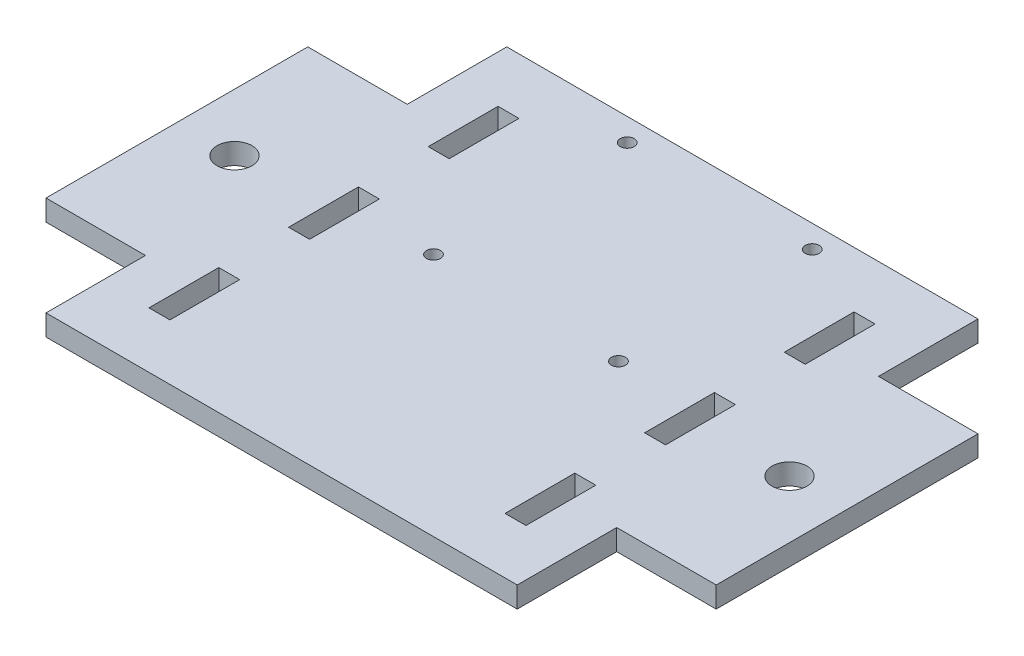
SolidWorks part; units mm, degrees
ref_plane "Front Plane" through (0, 0, 0) normal (0, 0, 1) x (1, 0, 0)
ref_plane "Top Plane" through (0, 0, 0) normal (0, 1, 0) x (1, 0, 0)
ref_plane "Right Plane" through (0, 0, 0) normal (1, 0, 0) x (0, 0, -1)
sketch "Sketch1" plane through (0, 0, 0) normal (0, 1, 0) x (1, 0, 0)
  line L0 (-48, 0) -> (48, 0) construction
  line L1 (-48, 33) -> (48, 33)
  line L2 (-48, 33) -> (-48, -33)
  line L3 (-48, -33) -> (48, -33)
  line L4 (48, 33) -> (48, -33)
  line L5 (-48, 33) -> (48, -33) construction
  line L6 (-48, -33) -> (48, 33) construction
  line L7 (0, 33) -> (0, -33) construction
  line L9 (17, 0) -> (-9.5, 0) construction
  line L13 (-13.25, 29.75) -> (13.25, 29.75) construction
  line L14 (-13.25, 29.75) -> (-13.25, 2) construction
  line L15 (-13.25, 2) -> (13.25, 2) construction
  line L16 (13.25, 29.75) -> (13.25, 2) construction
  circle A4 centre (-39.75, 0) radius 2.5
  circle A5 centre (39.75, 0) radius 2.5
  circle A6 centre (-13.25, 29.75) radius 1
  circle A7 centre (-13.25, 2) radius 1
  circle A8 centre (13.25, 2) radius 1
  circle A9 centre (13.25, 29.75) radius 1
  circle A10 centre (0, 0) radius 6 construction
  point P0 (0, 0)
  dimension "D6" = 27.75
  dimension "D7" = 26.5
  dimension "D8" = 2
  dimension "D9" = 2
  dimension "D10" = 5
  dimension "D11" = 8.25
  dimension "D12" = 12
  dimension "D4" = 2
  dimension "D5" = 2
  dimension "D13" = 34.75
  dimension "D1" = 96
  dimension "D2" = 66
  dimension "D3" = 2
extrude "Boss-Extrude1" add sketch "Sketch1" along normal blind 3
sketch "Sketch2" plane through (0, 3, 0) normal (0, 1, 0) x (1, 0, 0)
  line L0 (-48, 0) -> (48, 0) construction
  line L1 (-48, 33) -> (-48, -33) construction
  line L2 (48, -33) -> (48, 33) construction
  line L3 (0, 33) -> (0, -33) construction
  line L4 (48, 33) -> (-48, 33) construction
  line L5 (-48, -33) -> (48, -33) construction
  line L6 (33.75, 33) -> (33.75, 18.75)
  line L7 (-48, 33) -> (-33.75, 33)
  line L8 (-48, 33) -> (-48, 18.75)
  line L9 (-48, 18.75) -> (-33.75, 18.75)
  line L10 (-33.75, 33) -> (-33.75, 18.75)
  line L11 (48, 18.75) -> (33.75, 18.75)
  line L12 (48, 33) -> (48, 18.75)
  line L13 (48, 33) -> (33.75, 33)
  line L14 (48, -33) -> (33.75, -33)
  line L15 (48, -33) -> (48, -18.75)
  line L16 (48, -18.75) -> (33.75, -18.75)
  line L17 (33.75, -33) -> (33.75, -18.75)
  line L18 (-33.75, -33) -> (-33.75, -18.75)
  line L19 (-48, -18.75) -> (-33.75, -18.75)
  line L20 (-48, -33) -> (-48, -18.75)
  line L21 (-48, -33) -> (-33.75, -33)
  line L22 (-25.5, 33) -> (-25.5, -33) construction
  line L23 (25.5, 33) -> (25.5, -33) construction
  line L24 (-27, -25) -> (-24, -25)
  line L25 (-27, 5) -> (-24, 5)
  line L26 (-27, 5) -> (-27, -5)
  line L27 (-27, -5) -> (-24, -5)
  line L28 (-24, 5) -> (-24, -5)
  line L29 (-27, 5) -> (-24, -5) construction
  line L30 (-27, -5) -> (-24, 5) construction
  line L31 (-27, -15) -> (-27, -25)
  line L32 (-24, -15) -> (-24, -25)
  line L33 (-27, -15) -> (-24, -15)
  line L34 (-27, 15) -> (-24, 15)
  line L35 (-24, 15) -> (-24, 25)
  line L36 (-27, 15) -> (-27, 25)
  line L37 (-27, 25) -> (-24, 25)
  line L38 (27, -5) -> (24, 5) construction
  line L39 (27, 5) -> (24, -5) construction
  line L40 (27, 25) -> (24, 25)
  line L41 (27, 15) -> (27, 25)
  line L42 (24, 15) -> (24, 25)
  line L43 (27, 15) -> (24, 15)
  line L44 (27, -15) -> (24, -15)
  line L45 (24, -15) -> (24, -25)
  line L46 (27, -15) -> (27, -25)
  line L47 (24, 5) -> (24, -5)
  line L48 (27, -5) -> (24, -5)
  line L49 (27, 5) -> (27, -5)
  line L50 (27, 5) -> (24, 5)
  line L51 (27, -25) -> (24, -25)
  point P33 (-25.5, 0)
  point P58 (25.5, 0)
  dimension "D1" = 14.25
  dimension "D2" = 14.25
  dimension "D3" = 22.5
  dimension "D4" = 22.5
  dimension "D5" = 3
  dimension "D6" = 10
  dimension "D7" = 2
extrude "Cut-Extrude1" cut sketch "Sketch2" against normal blind 3
